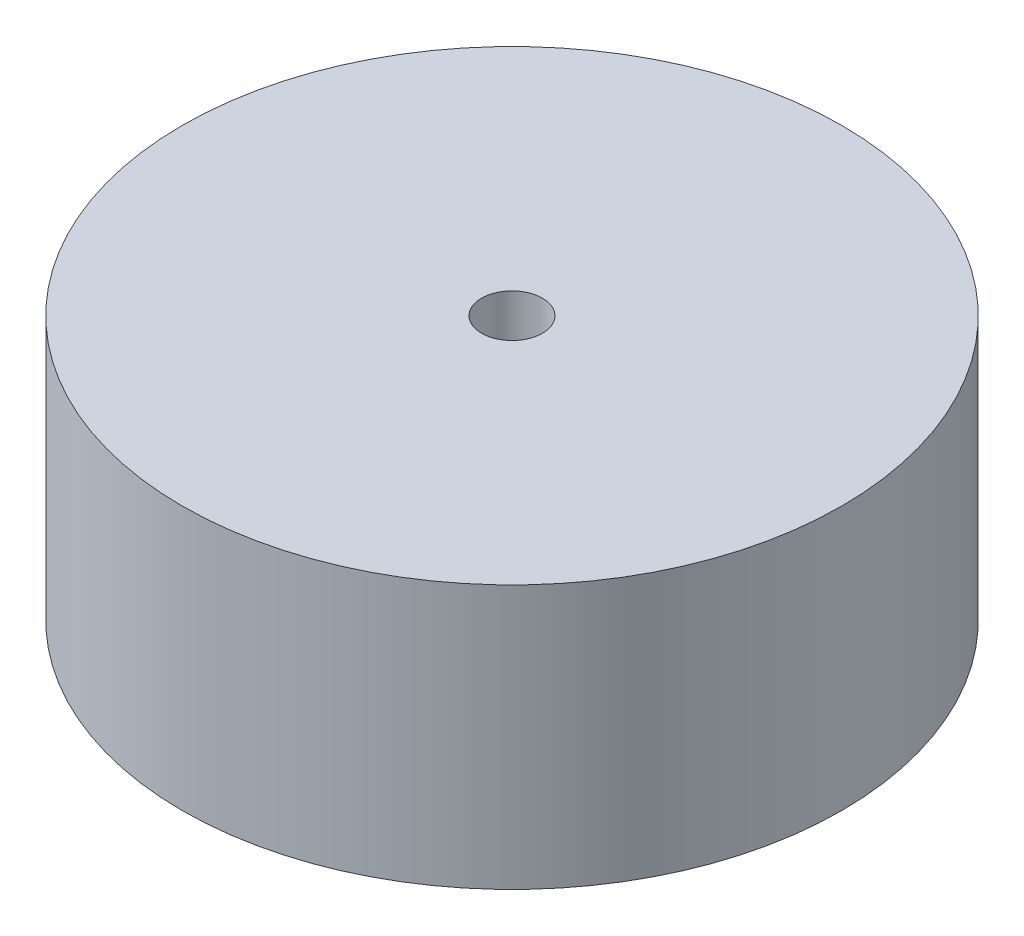
SolidWorks part; units mm, degrees
material "硅橡胶"
ref_plane "前视基准面" through (0, 0, 0) normal (0, 0, 1) x (1, 0, 0)
ref_plane "上视基准面" through (0, 0, 0) normal (0, 1, 0) x (1, 0, 0)
ref_plane "右视基准面" through (0, 0, 0) normal (1, 0, 0) x (0, 0, -1)
other "Configuration Table"
sketch "草图1" plane through (0, 0, 0) normal (0, 1, 0) x (1, 0, 0)
  circle A0 centre (0, 0) radius 32.5
  dimension "D1" = 65
extrude "凸台-拉伸1" add sketch "草图1" along normal blind 26
sketch "草图2" plane through (0, 0, 0) normal (0, -1, 0) x (1, 0, 0)
  circle A0 centre (0, 0) radius 6
  dimension "D1" = 12
extrude "凸台-拉伸2" add sketch "草图2" along normal blind 4
sketch "草图3" plane through (0, -4, 0) normal (0, -1, 0) x (1, 0, 0)
  circle A0 centre (0, 0) radius 3
extrude "切除-拉伸1" cut sketch "草图3" against normal blind 52
